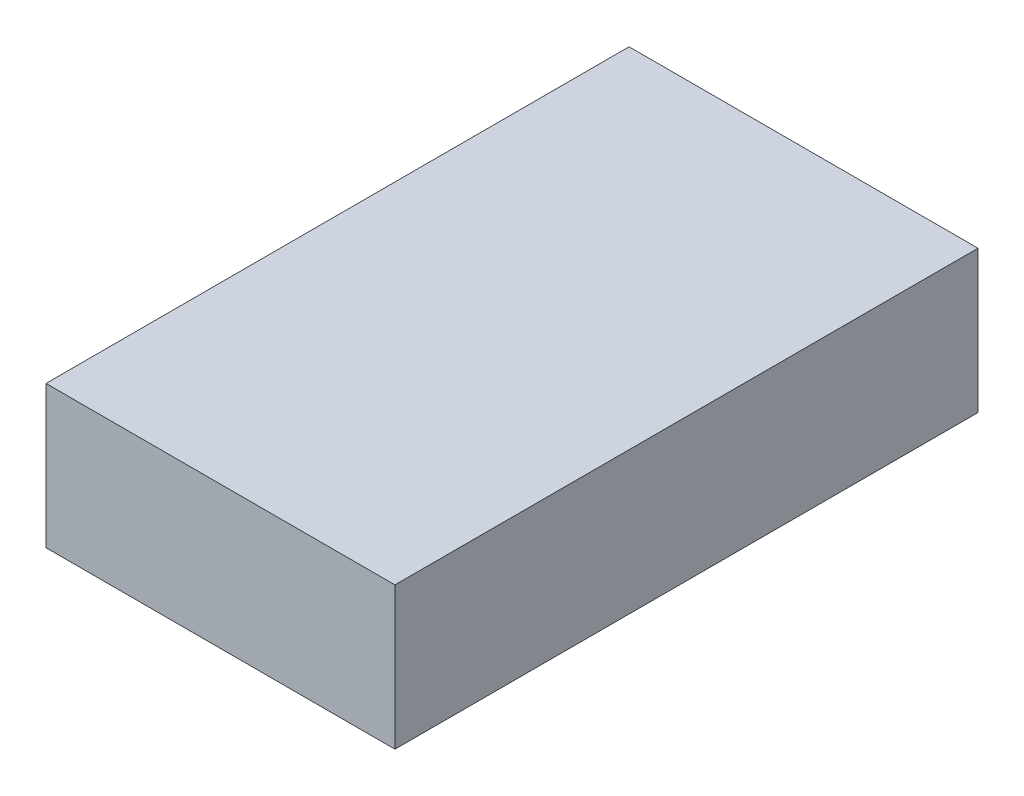
SolidWorks part; units mm, degrees
ref_plane "Front Plane" through (0, 0, 0) normal (0, 0, 1) x (1, 0, 0)
ref_plane "Top Plane" through (0, 0, 0) normal (0, 1, 0) x (1, 0, 0)
ref_plane "Right Plane" through (0, 0, 0) normal (1, 0, 0) x (0, 0, -1)
sketch "Sketch1" plane through (0, 0, 0) normal (0, 1, 0) x (1, 0, 0)
  line L1 (0, 0) -> (76, 0)
  line L2 (0, 0) -> (0, 127)
  line L3 (0, 127) -> (76, 127)
  line L4 (76, 0) -> (76, 127)
  dimension "D1" = 76
  dimension "D2" = 127
extrude "Boss-Extrude1" add sketch "Sketch1" along normal blind 31
